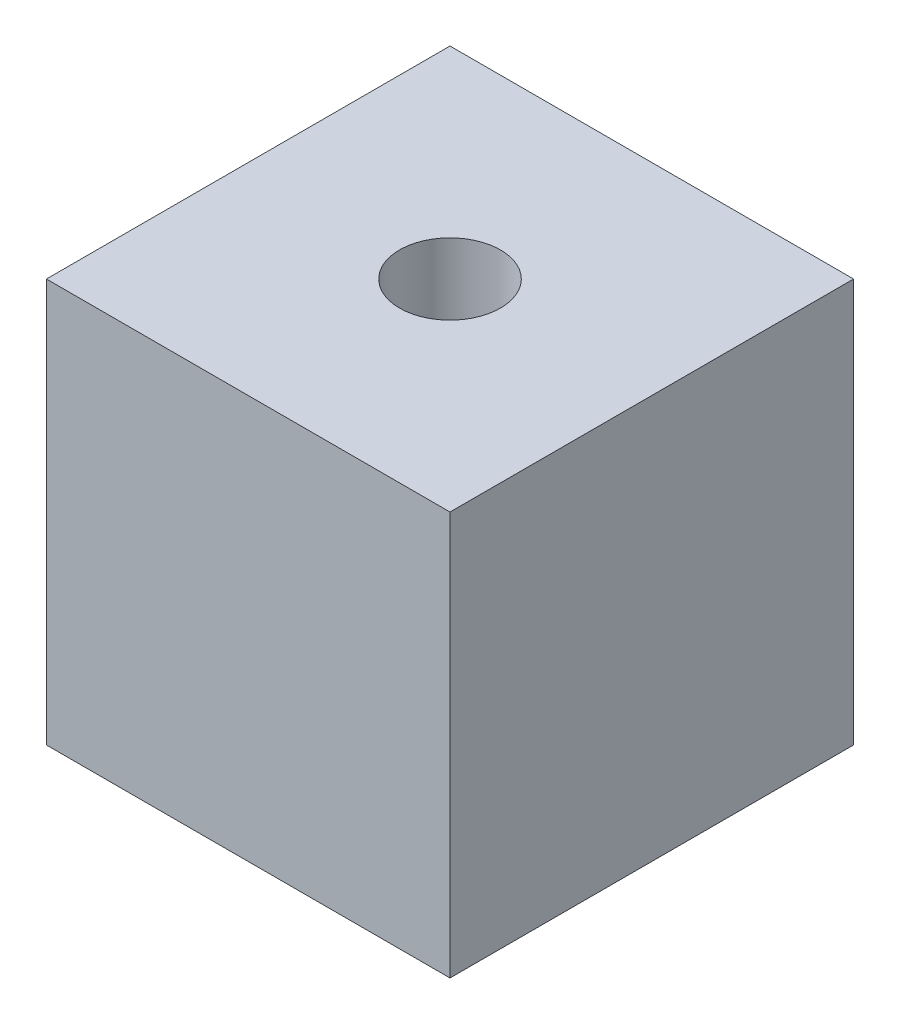
SolidWorks part; units mm, degrees
ref_plane "Front Plane" through (0, 0, 0) normal (0, 0, 1) x (1, 0, 0)
ref_plane "Top Plane" through (0, 0, 0) normal (0, 1, 0) x (1, 0, 0)
ref_plane "Right Plane" through (0, 0, 0) normal (1, 0, 0) x (0, 0, -1)
sketch "Sketch1" plane through (0, 0, 0) normal (0, 1, 0) x (1, 0, 0)
  line L1 (0, 0) -> (20, 0)
  line L2 (0, 0) -> (0, -20)
  line L3 (0, -20) -> (20, -20)
  line L4 (20, 0) -> (20, -20)
  circle A0 centre (10, -10) radius 2.5
  dimension "D3" = 5
  dimension "D1" = 20
  dimension "D2" = 20
extrude "Boss-Extrude1" add sketch "Sketch1" along normal blind 20
